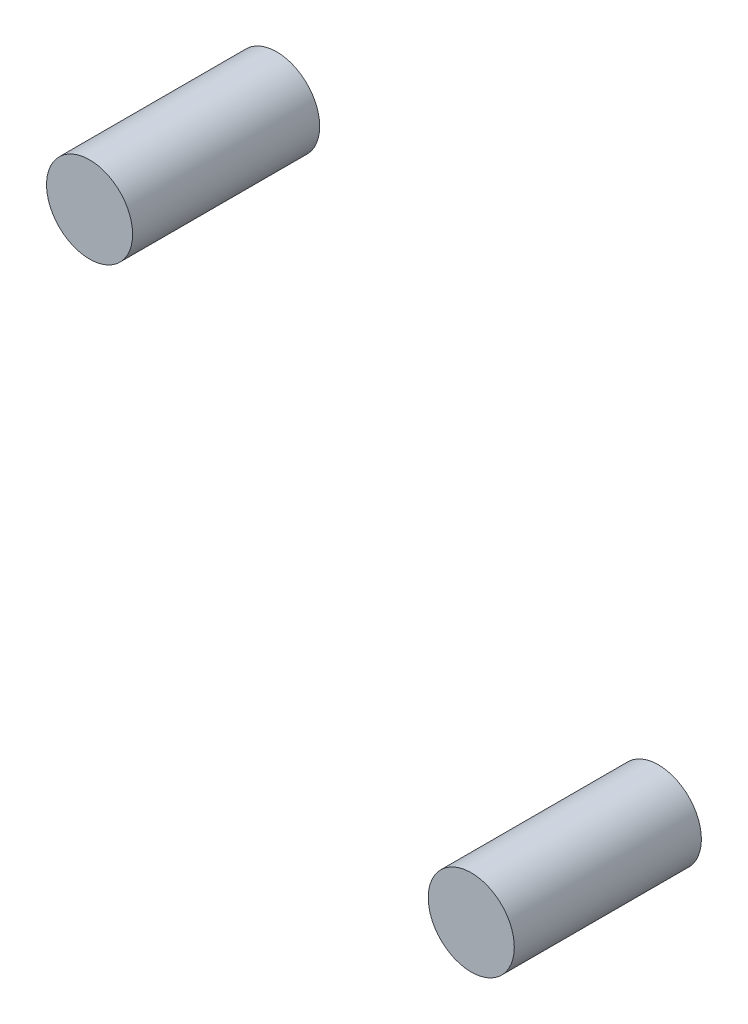
SolidWorks part; units mm, degrees
ref_plane "前视基准面" through (0, 0, 0) normal (0, 0, 1) x (1, 0, 0)
ref_plane "上视基准面" through (0, 0, 0) normal (0, 1, 0) x (1, 0, 0)
ref_plane "右视基准面" through (0, 0, 0) normal (1, 0, 0) x (0, 0, -1)
sketch "草图1" plane through (0, 0, 0) normal (0, 0, 1) x (1, 0, 0)
  circle A0 centre (16.4478, 49.169) radius 5.75
  circle A1 centre (67.4478, -7.831) radius 5.75
  dimension "D1" = 11.5
  dimension "D2" = 57
  dimension "D3" = 51
extrude "凸台-拉伸1" add sketch "草图1" along normal blind 25
